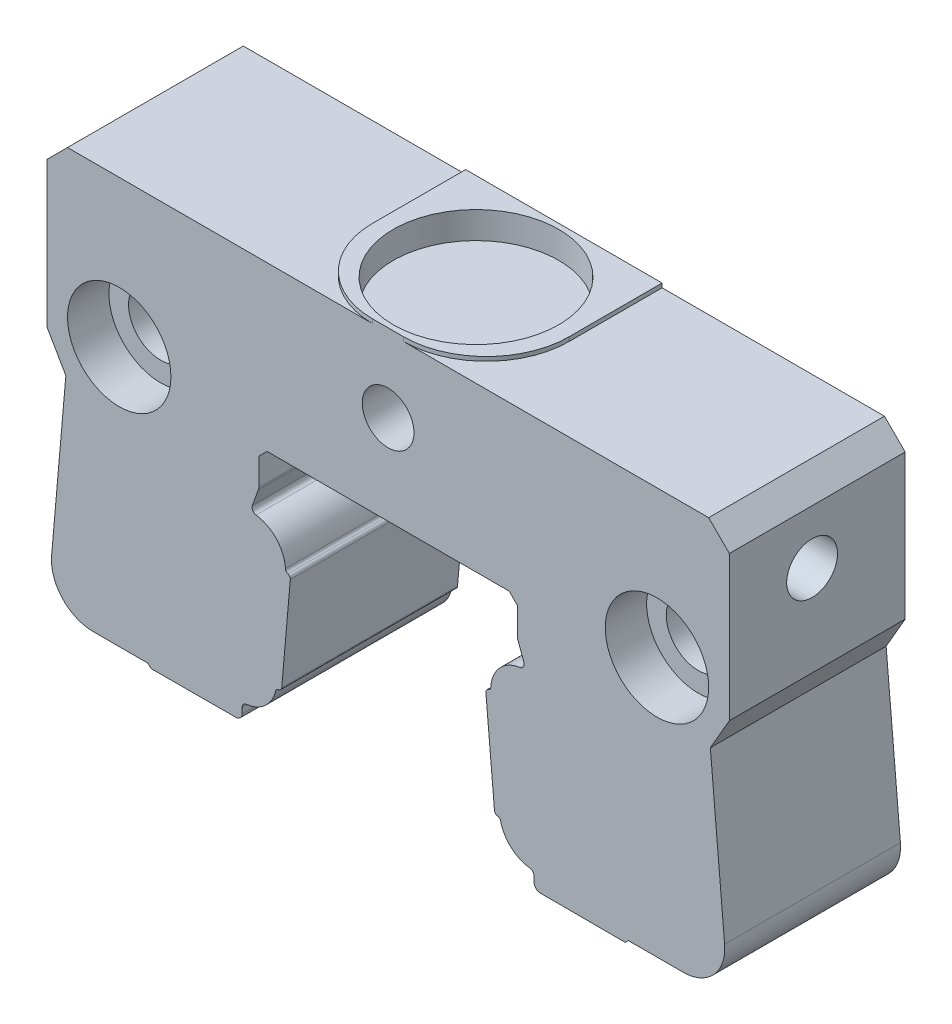
SolidWorks part; units mm, degrees
ref_plane "Front Plane" through (0, 0, 0) normal (0, 0, 1) x (1, 0, 0)
ref_plane "Top Plane" through (0, 0, 0) normal (0, 1, 0) x (1, 0, 0)
ref_plane "Right Plane" through (0, 0, 0) normal (1, 0, 0) x (0, 0, -1)
sketch "Sketch1" plane through (0, 0, 0) normal (0, 0, 1) x (1, 0, 0)
  line L78 (4.9255, -3.0009) -> (5.3403, -7.7418)
  line L79 (7.2543, -9.5204) -> (7.2543, -10.0895)
  line L80 (7.2543, -10.0895) -> (11.6633, -10.1)
  line L81 (11.6633, -10.1) -> (11.8133, -9.95)
  line L82 (11.8133, -9.95) -> (14.4753, -9.95)
  line L83 (16.4676, -7.7757) -> (15.7779, 0.1078)
  line L84 (15.7779, 0.1078) -> (16.6972, 1.7)
  line L85 (16.6972, 1.7) -> (16.6972, 8.7)
  line L86 (16.6972, 8.7) -> (15.6972, 9.7)
  line L87 (15.6972, 9.7) -> (-15.3028, 9.7)
  line L88 (-15.3028, 9.7) -> (-16.3028, 8.7)
  line L89 (-16.3028, 8.7) -> (-16.3028, 1.7)
  line L90 (-16.3028, 1.7) -> (-15.3835, 0.1078)
  line L91 (-15.3835, 0.1078) -> (-16.0733, -7.7757)
  line L92 (-14.0809, -9.95) -> (-11.419, -9.95)
  line L93 (-11.419, -9.95) -> (-11.269, -10.1)
  line L94 (-11.269, -10.1) -> (-6.86, -10.0895)
  line L95 (-6.86, -10.0895) -> (-6.86, -9.5204)
  line L96 (-4.9459, -7.7418) -> (-4.5311, -3.0009)
  line L97 (-6.3687, -0.8255) -> (-6.0709, -0.0072)
  line L98 (-6.0528, 0.0954) -> (-6.0528, 1.4)
  line L99 (-6.0528, 1.4) -> (-5.6528, 1.8)
  line L100 (-5.6528, 1.8) -> (6.0472, 1.8)
  line L101 (6.0472, 1.8) -> (6.4472, 1.4)
  line L102 (6.4472, 1.4) -> (6.4472, 0.0954)
  line L103 (6.4653, -0.0072) -> (6.7631, -0.8255)
  arc A69 (6.7769, -0.9039) -> (6.7631, -0.8255) centre (6.5479, -0.9039) ccw
  arc A70 (6.5787, -1.1308) -> (6.7769, -0.9039) centre (6.5479, -0.9039) ccw
  arc A71 (6.5787, -1.1308) -> (5.1605, -2.6699) centre (6.7992, -2.7569) ccw
  arc A72 (5.0428, -2.8234) -> (5.1605, -2.6699) centre (4.9898, -2.6609) ccw
  arc A73 (5.0428, -2.8234) -> (4.9255, -3.0009) centre (5.0959, -2.986) ccw
  arc A74 (5.3403, -7.7418) -> (5.4896, -7.8966) centre (5.5106, -7.7269) ccw
  arc A75 (5.6353, -8.0281) -> (5.4896, -7.8966) centre (5.4686, -8.0663) ccw
  arc A76 (5.6353, -8.0281) -> (7.051, -9.2929) centre (7.235, -7.6622) ccw
  arc A77 (7.2543, -9.5204) -> (7.051, -9.2929) centre (7.0253, -9.5204) ccw
  arc A78 (14.4753, -9.95) -> (16.4753, -7.95) centre (14.4753, -7.95) ccw
  arc A79 (16.4753, -7.95) -> (16.4676, -7.7757) centre (14.4753, -7.95) ccw
  arc A80 (-16.0733, -7.7757) -> (-14.0809, -9.95) centre (-14.0809, -7.95) ccw
  arc A81 (-6.6566, -9.2929) -> (-6.86, -9.5204) centre (-6.631, -9.5204) ccw
  arc A82 (-6.6566, -9.2929) -> (-5.241, -8.0281) centre (-6.8406, -7.6622) ccw
  arc A83 (-5.0953, -7.8966) -> (-5.241, -8.0281) centre (-5.0743, -8.0663) ccw
  arc A84 (-5.0953, -7.8966) -> (-4.9459, -7.7418) centre (-5.1163, -7.7269) ccw
  arc A85 (-4.5311, -3.0009) -> (-4.5305, -2.986) centre (-4.7015, -2.986) ccw
  arc A86 (-4.5305, -2.986) -> (-4.6484, -2.8234) centre (-4.7015, -2.986) ccw
  arc A87 (-4.7662, -2.6699) -> (-4.6484, -2.8234) centre (-4.5954, -2.6609) ccw
  arc A88 (-4.7662, -2.6699) -> (-6.1843, -1.1308) centre (-6.4049, -2.7569) ccw
  arc A89 (-6.3687, -0.8255) -> (-6.1843, -1.1308) centre (-6.1536, -0.9039) ccw
  arc A90 (-6.0709, -0.0072) -> (-6.0528, 0.0954) centre (-6.3528, 0.0954) ccw
  arc A91 (6.4472, 0.0954) -> (6.4653, -0.0072) centre (6.7472, 0.0954) ccw
extrude "Extrude1" add sketch "Sketch1" along normal mid plane 8.5
ref_plane "MID PLANE" through (0.1972, 0, 0) normal (-1, 0, 0) x (0, 0, 1)
hole_wizard "CBORE for M5 Hex Head Bolt2" positions "3DSketch3" profile "Sketch10" counterbore size "M5" standard "Ansi Metric" end condition through all
sketch3d "3DSketch3"
  line L1 (0, 0, 0) -> (0, 13.0953, 0) construction
  point P0 (-12.8028, 2.5964, 4.25)
  point P2 (13.1972, 2.5964, 4.25)
  dimension "D1" = 12.7
  dimension "D3" = 26
  dimension "D4" = 13
sketch "Sketch10" plane through (-12.8028, 2.5964, 4.25) normal (1, 0, 0) x (0, -1, 0)
  line L0 (0, 0) -> (0, 8.5)
  line L1 (0, 8.5) -> (1.55, 8.5)
  line L3 (1.55, 8.5) -> (1.55, 2)
  line L4 (1.55, 2) -> (2.5, 2)
  line L5 (2.5, 2) -> (2.5, 0)
  line L7 (2.5, 0) -> (0, 0)
  line L11 (0, -6.35) -> (0, 107.95) construction
  dimension "Thru Hole Dia." = 3.1
  dimension "Thru Hole Depth" = 8.5
  dimension "C'Bore Dia." = 5
  dimension "C'Bore Depth" = 2
hole_wizard "Ø2.5 (2.5) Diameter Hole1" positions "3DSketch4" profile "Sketch11" hole size "Ø2.5" standard "Ansi Metric"
sketch3d "3DSketch4"
  point P0 (0.1972, 6.1272, 4.25)
  dimension "D2" = 16.2
sketch "Sketch11" plane through (0.1972, 6.1272, 4.25) normal (1, 0, 0) x (0, -1, 0)
  line L0 (0, 0) -> (0, 6.7511)
  line L1 (0, 6.7511) -> (1.25, 6)
  line L2 (1.25, 6) -> (1.25, 0)
  line L5 (1.25, 0) -> (0, 0)
  line L10 (0, 6.7511) -> (-1.25, 6) construction
  line L11 (0, -6.35) -> (0, 107.95) construction
  dimension "Hole Dia." = 2.5
  dimension "Hole Depth" = 6
  dimension "Drill Angle" = 118
sketch "Sketch13" plane through (0, 9.7, 0) normal (0, 1, 0) x (1, 0, 0)
  line L0 (0.1972, 0) -> (0.1972, 10.7539) construction
  line L1 (-4.5528, 4.25) -> (-4.5528, -0.25)
  line L2 (4.9472, 4.25) -> (4.9472, -0.25)
  line L4 (0.1972, 3.85) -> (0.1972, -3.85) construction
  line L5 (15.6972, 4.25) -> (-15.3028, 4.25) construction
  line L6 (4.9472, 4.25) -> (-4.5528, 4.25)
  line L7 (15.6972, -4.25) -> (-15.3028, -4.25) construction
  line L8 (0.9472, -4.25) -> (-0.5528, -4.25)
  arc A0 (4.9472, -0.25) -> (0.9472, -4.25) centre (0.9472, -0.25) cw
  arc A2 (-4.5528, -0.25) -> (-0.5528, -4.25) centre (-0.5528, -0.25) ccw
  circle A3 centre (0.1972, 0) radius 4
  dimension "D1" = 9.5
  dimension "D2" = 4
  dimension "D3" = 8
  dimension "D4" = 4.25
extrude "Extrude3" add sketch "Sketch13" along normal blind 0.2
sketch "Sketch15" plane through (0, 9.9, 0) normal (0, 1, 0) x (1, 0, 0)
  circle A0 centre (0.1972, 0) radius 4
  circle A1 centre (0.1972, 0) radius 4 construction
extrude "Cut-Extrude2" cut sketch "Sketch15" against normal blind 1.3
fillet "Fillet1" radius 0.3 2 edges at (7.2543, -10.0895, 0) (-6.86, -10.0895, 0)
ref_plane "Plane1" through (0.0145, 6.1277, 0) normal (-0.0024, -1, 0) x (1, -0.0024, 0)
sketch "Sketch16" plane through (0.0145, 6.1277, 0) normal (-0.0024, -1, 0) x (1, -0.0024, 0)
  line L0 (-24.602, 0.25) -> (20.3051, 0.25) construction
  line L2 (-14.0572, 4.25) -> (-16.062, 4.25) construction
  line L3 (16.6931, 1.48) -> (12.1931, 1.48)
  line L4 (16.6931, 4.25) -> (16.6931, -4.25) construction
  line L5 (12.1931, 1.48) -> (12.1931, 0.25)
  line L6 (12.1931, 0.25) -> (16.6931, 0.25)
  line L7 (16.6931, 0.25) -> (16.6931, 1.48)
  line L8 (-16.3234, 4.25) -> (-16.3234, -4.25) construction
  line L9 (-16.3234, 1.48) -> (-11.8234, 1.48)
  line L11 (-11.8234, 1.48) -> (-11.8234, 0.25)
  line L12 (-11.8234, 0.25) -> (-16.3234, 0.25)
  line L13 (-16.3234, 1.48) -> (-16.3234, 0.25)
  dimension "D1" = 4
  dimension "D2" = 2.46
  dimension "D3" = 4.5
revolve "Cut-Revolve1" cut sketch "Sketch16" angle 360 about L0
